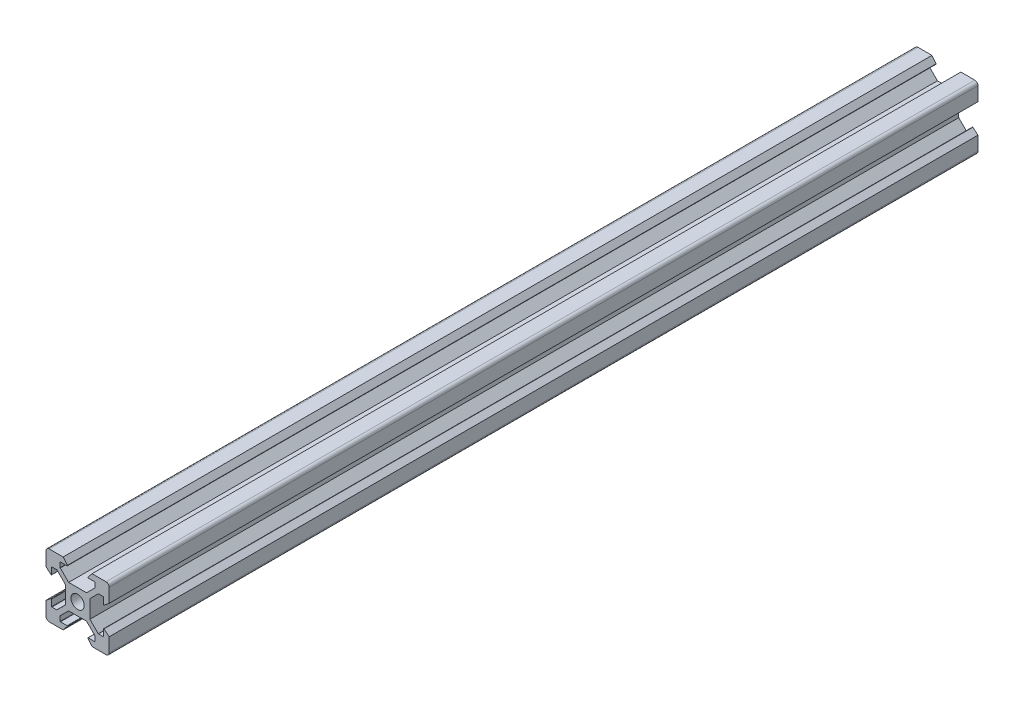
SolidWorks part; units mm, degrees
material "Aleación 6061"
ref_plane "Front Plane" through (0, 0, 0) normal (0, 0, 1) x (1, 0, 0)
ref_plane "Top Plane" through (0, 0, 0) normal (0, 1, 0) x (1, 0, 0)
ref_plane "Right Plane" through (0, 0, 0) normal (1, 0, 0) x (0, 0, -1)
sketch "Sketch1" plane through (0, 0, 0) normal (0, 0, 1) x (1, 0, 0)
  line L0 (-2.8393, 3.9) -> (-5.4707, 6.5314)
  line L1 (-10, 10) -> (-4.58, 10)
  line L2 (-10, 10) -> (-10, 4.58)
  line L3 (-10, -10) -> (-4.58, -10)
  line L4 (10, 10) -> (10, 4.58)
  line L5 (-10, 10) -> (-3.9, 3.9) construction
  line L6 (-10, -10) -> (-4.061, -4.061) construction
  line L7 (-2.8393, 3.9) -> (2.8393, 3.9)
  line L8 (-3.9, 2.8393) -> (-3.9, -2.8393)
  line L9 (-2.8393, -3.9) -> (2.8393, -3.9)
  line L10 (3.9, 2.8393) -> (3.9, -2.8393)
  line L11 (-1.4849, 1.4849) -> (3.9, -3.9) construction
  line L12 (-3.9, -3.9) -> (1.4849, 1.4849) construction
  line L13 (-5.5, 6.6021) -> (-5.5, 8.1)
  line L14 (-5.4, 8.2) -> (-3.3344, 8.2)
  line L15 (-3.2566, 8.3629) -> (-4.58, 10)
  line L16 (0, 0) -> (0, 5.2663) construction
  line L17 (-3.9, 2.8393) -> (-6.5314, 5.4707)
  line L18 (-6.6021, 5.5) -> (-8.1, 5.5)
  line L19 (-8.2, 5.4) -> (-8.2, 3.3344)
  line L20 (-8.3629, 3.2566) -> (-10, 4.58)
  line L21 (8.3629, 3.2566) -> (10, 4.58)
  line L22 (8.2, 5.4) -> (8.2, 3.3344)
  line L23 (6.6021, 5.5) -> (8.1, 5.5)
  line L24 (3.9, 2.8393) -> (6.5314, 5.4707)
  line L25 (3.2566, 8.3629) -> (4.58, 10)
  line L26 (5.4, 8.2) -> (3.3344, 8.2)
  line L27 (2.8393, 3.9) -> (5.4707, 6.5314)
  line L28 (5.5, 6.6021) -> (5.5, 8.1)
  line L29 (55, 0) -> (-55, 0) construction
  line L30 (-8.3629, -3.2566) -> (-10, -4.58)
  line L31 (-8.2, -5.4) -> (-8.2, -3.3344)
  line L32 (-6.6021, -5.5) -> (-8.1, -5.5)
  line L33 (-3.9, -2.8393) -> (-6.5314, -5.4707)
  line L34 (-2.8393, -3.9) -> (-5.4707, -6.5314)
  line L35 (-5.5, -6.6021) -> (-5.5, -8.1)
  line L36 (-5.4, -8.2) -> (-3.3344, -8.2)
  line L37 (-3.2566, -8.3629) -> (-4.58, -10)
  line L38 (8.3629, -3.2566) -> (10, -4.58)
  line L39 (8.2, -5.4) -> (8.2, -3.3344)
  line L40 (6.6021, -5.5) -> (8.1, -5.5)
  line L41 (3.9, -2.8393) -> (6.5314, -5.4707)
  line L42 (2.8393, -3.9) -> (5.4707, -6.5314)
  line L43 (5.5, -6.6021) -> (5.5, -8.1)
  line L44 (5.4, -8.2) -> (3.3344, -8.2)
  line L45 (3.2566, -8.3629) -> (4.58, -10)
  line L46 (3.9, 3.9) -> (10, 10) construction
  line L47 (3.2459, -3.2459) -> (10, -10) construction
  line L48 (-10, -4.58) -> (-10, -10)
  line L49 (4.58, -10) -> (10, -10)
  line L50 (10, -4.58) -> (10, -10)
  line L51 (4.58, 10) -> (10, 10)
  circle A0 centre (0, 0) radius 2.1
  arc A1 (-5.4707, 6.5314) -> (-5.5, 6.6021) centre (-5.4, 6.6021) cw
  arc A2 (-5.5, 8.1) -> (-5.4, 8.2) centre (-5.4, 8.1) cw
  arc A3 (-3.3344, 8.2) -> (-3.2566, 8.3629) centre (-3.3344, 8.3) ccw
  arc A4 (-6.5314, 5.4707) -> (-6.6021, 5.5) centre (-6.6021, 5.4) ccw
  arc A5 (-8.1, 5.5) -> (-8.2, 5.4) centre (-8.1, 5.4) ccw
  arc A6 (-8.2, 3.3344) -> (-8.3629, 3.2566) centre (-8.3, 3.3344) cw
  arc A7 (8.2, 3.3344) -> (8.3629, 3.2566) centre (8.3, 3.3344) ccw
  arc A8 (8.1, 5.5) -> (8.2, 5.4) centre (8.1, 5.4) cw
  arc A9 (6.5314, 5.4707) -> (6.6021, 5.5) centre (6.6021, 5.4) cw
  arc A10 (3.3344, 8.2) -> (3.2566, 8.3629) centre (3.3344, 8.3) cw
  arc A11 (5.5, 8.1) -> (5.4, 8.2) centre (5.4, 8.1) ccw
  arc A12 (5.4707, 6.5314) -> (5.5, 6.6021) centre (5.4, 6.6021) ccw
  arc A13 (-8.2, -3.3344) -> (-8.3629, -3.2566) centre (-8.3, -3.3344) ccw
  arc A14 (-8.1, -5.5) -> (-8.2, -5.4) centre (-8.1, -5.4) cw
  arc A15 (-6.5314, -5.4707) -> (-6.6021, -5.5) centre (-6.6021, -5.4) cw
  arc A16 (-5.4707, -6.5314) -> (-5.5, -6.6021) centre (-5.4, -6.6021) ccw
  arc A17 (-5.5, -8.1) -> (-5.4, -8.2) centre (-5.4, -8.1) ccw
  arc A18 (-3.3344, -8.2) -> (-3.2566, -8.3629) centre (-3.3344, -8.3) cw
  arc A19 (8.2, -3.3344) -> (8.3629, -3.2566) centre (8.3, -3.3344) cw
  arc A20 (8.1, -5.5) -> (8.2, -5.4) centre (8.1, -5.4) ccw
  arc A21 (6.5314, -5.4707) -> (6.6021, -5.5) centre (6.6021, -5.4) ccw
  arc A22 (5.4707, -6.5314) -> (5.5, -6.6021) centre (5.4, -6.6021) cw
  arc A23 (5.5, -8.1) -> (5.4, -8.2) centre (5.4, -8.1) cw
  arc A24 (3.3344, -8.2) -> (3.2566, -8.3629) centre (3.3344, -8.3) ccw
  point P0 (0, 0)
  point P6 (0, 0)
  point P25 (-3.125, 8.2)
  dimension "D5" = 4.2
  dimension "D11" = 0.1
  dimension "D1" = 20
  dimension "D3" = 7.8
  dimension "D4" = 7.8
  dimension "D6" = 0.75
  dimension "D7" = 4.3
  dimension "D8" = 4.58
  dimension "D9" = 3.125
  dimension "D10" = 5.5
extrude "Boss-Extrude1" add sketch "Sketch1" along normal blind 275
fillet "Fillet1" radius 1 4 edges at (10, -10, 137.5) (10, 10, 137.5) (-10, -10, 137.5) (-10, 10, 137.5)
